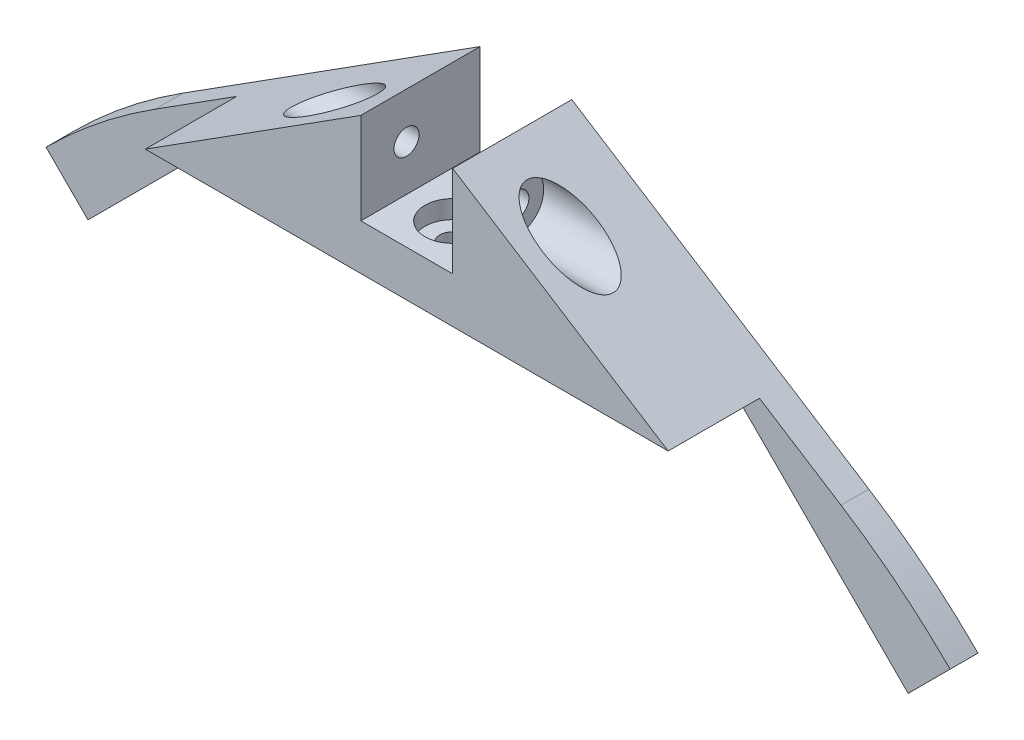
SolidWorks part; units mm, degrees
ref_plane "Front Plane" through (0, 0, 0) normal (0, 0, 1) x (1, 0, 0)
ref_plane "Top Plane" through (0, 0, 0) normal (0, 1, 0) x (1, 0, 0)
ref_plane "Right Plane" through (0, 0, 0) normal (1, 0, 0) x (0, 0, -1)
sketch "Sketch1" plane through (0, 0, 0) normal (0, 0, 1) x (1, 0, 0)
  line L0 (0, 284.5128) -> (0, -315.9314) construction
  line L1 (-464.297, 0) -> (544.589, 0) construction
  line L2 (-129.5, 50.1051) -> (-50.1051, 129.5)
  line L9 (-129.5, 50.1051) -> (-129.5, -50.1051)
  line L11 (-50.1051, -129.5) -> (50.1051, -129.5)
  line L13 (129.5, -50.1051) -> (129.5, 50.1051)
  line L15 (50.1051, 129.5) -> (-50.1051, 129.5)
  line L17 (50.1051, 129.5) -> (129.5, 50.1051)
  line L18 (129.5, -50.1051) -> (50.1051, -129.5)
  line L19 (-50.1051, -129.5) -> (-129.5, -50.1051)
  line L20 (-53.6407, 129.5) -> (-91.5703, 91.5703)
  line L21 (-91.5703, -91.5703) -> (-53.6407, -129.5)
  line L22 (53.6407, -129.5) -> (91.5703, -91.5703)
  line L23 (129.5, 53.6407) -> (91.5703, 91.5703)
  circle A0 centre (0, 0) radius 129.5 construction
  circle A2 centre (0, 0) radius 129.5
  circle A3 centre (0, 0) radius 109.75
  dimension "D2" = 259
  dimension "D3" = 219.5
  dimension "D1" = 0
  dimension "D4" = 259
  dimension "D5" = 254
  dimension "D6" = 4
sketch "Sketch2" plane through (0, 0, 0) normal (0, 0, 1) x (1, 0, 0)
  circle A2 centre (0, 0) radius 109.75
  circle A3 centre (0, 0) radius 129.5
  point P1 (114.75, 0)
  point P3 (0, 0)
  point P9 (104.9544, 32.0878)
  dimension "D1" = 219.5
  dimension "D2" = 259
sketch "Sketch3" plane through (0, 0, 0) normal (0, 0, 1) x (1, 0, 0)
  line L0 (0, 216.6703) -> (0, -179.3029) construction
  line L2 (0, 284.5128) -> (0, -315.9314) construction
  line L4 (-261.0178, 0) -> (186.7113, 0) construction
  line L5 (-464.297, 0) -> (544.589, 0) construction
  line L22 (-157.8941, 129.5) -> (159.8749, 129.5) construction
  line L23 (0, 0) -> (0, 188.0938) construction
  line L40 (-94.2678, 129.5) -> (106.7846, 129.5) construction
  line L41 (129.5, -10) -> (109.5, -10)
  line L42 (10, 129.5) -> (-10, 129.5)
  line L43 (10, 129.5) -> (10, 109.5)
  line L44 (10, 109.5) -> (-10, 109.5)
  line L45 (-10, 129.5) -> (-10, 109.5)
  line L46 (129.5, -10) -> (129.5, 10)
  line L47 (129.5, 10) -> (109.5, 10)
  line L48 (109.5, -10) -> (109.5, 10)
  line L49 (-10, -129.5) -> (-10, -109.5)
  line L50 (-10, -129.5) -> (10, -129.5)
  line L51 (10, -129.5) -> (10, -109.5)
  line L52 (-10, -109.5) -> (10, -109.5)
  line L53 (-129.5, 10) -> (-109.5, 10)
  line L54 (-129.5, 10) -> (-129.5, -10)
  line L55 (-129.5, -10) -> (-109.5, -10)
  line L56 (-109.5, 10) -> (-109.5, -10)
  line L57 (-22.9682, 119.5) -> (92.755, 119.5) construction
  circle A8 centre (-15, 119.5) radius 2.75
  circle A9 centre (15, 119.5) radius 2.75
  circle A10 centre (119.5, 15) radius 2.75
  circle A11 centre (119.5, -15) radius 2.75
  circle A12 centre (15, -119.5) radius 2.75
  circle A13 centre (-15, -119.5) radius 2.75
  circle A14 centre (-119.5, -15) radius 2.75
  circle A15 centre (-119.5, 15) radius 2.75
  dimension "D8" = 5.5
  dimension "D9" = 15
  dimension "D1" = 129.5
  dimension "D2" = 0
  dimension "D3" = 90
  dimension "D4" = 129.5
  dimension "D5" = 20
  dimension "D7" = 10
  dimension "D6" = 20
  dimension "D10" = 10
  dimension "D12" = 4
  dimension "D11" = 4
sketch "Sketch5" plane through (0, 0, 0) normal (0, 0, 1) x (1, 0, 0)
  line L0 (0, 161.9102) -> (0, -158.9824) construction
  line L1 (0, 284.5128) -> (0, -315.9314) construction
  line L11 (-129.5, 50.1051) -> (-50.1051, 129.5) construction
  line L12 (50.1051, 129.5) -> (-50.1051, 129.5) construction
  line L13 (50.1051, 129.5) -> (129.5, 50.1051) construction
  line L14 (-89.8026, 89.8026) -> (-50.1051, 129.5)
  line L15 (50.1051, 129.5) -> (-50.1051, 129.5)
  line L16 (50.1051, 129.5) -> (89.8026, 89.8026)
  line L17 (89.8026, 89.8026) -> (98.9949, 98.9949)
  line L18 (-89.8026, 89.8026) -> (-98.9949, 98.9949)
  arc A5 (98.9949, 98.9949) -> (-98.9949, 98.9949) centre (0, 0) ccw
  dimension "D2" = 280
extrude "Boss-Extrude4" add sketch "Sketch5" against normal blind 6.1
sketch "Sketch6" plane through (0, 0, 0) normal (0, 0, 1) x (1, 0, 0)
  line L0 (0, 251.9094) -> (0, -160.8611) construction
  line L1 (0, 284.5128) -> (0, -315.9314) construction
  line L2 (10.05, 139.5) -> (-10.05, 139.5)
  line L3 (-10.05, 139.5) -> (-10.05, 159.5)
  line L4 (-10.05, 159.5) -> (-50.1051, 130.7267)
  line L5 (-50.1051, 130.7267) -> (-50.1051, 129.5)
  line L6 (-50.1051, 129.5) -> (50.1051, 129.5)
  line L7 (50.1051, 129.5) -> (-50.1051, 129.5) construction
  line L8 (50.1051, 130.7267) -> (50.1051, 129.5)
  line L9 (10.05, 159.5) -> (50.1051, 130.7267)
  line L10 (10.05, 139.5) -> (10.05, 159.5)
  arc A0 (98.9949, 98.9949) -> (-98.9949, 98.9949) centre (0, 0) ccw construction
  point P18 (0, 129.5)
  point P21 (0, 139.5)
  dimension "D1" = 139.5
  dimension "D2" = 10.05
  dimension "D3" = 20
extrude "Boss-Extrude5" add sketch "Sketch6" along normal blind 20
sketch "Sketch7" plane through (0, 0, 0) normal (0, 0, 1) x (1, 0, 0)
  line L0 (-10.05, 159.5) -> (-75.1007, 118.152)
  line L1 (-129.5, 50.1051) -> (-50.1051, 129.5) construction
  line L2 (-98.9949, 98.9949) -> (-89.8026, 89.8026) construction
  line L3 (-89.8026, 89.8026) -> (-50.1051, 129.5)
  line L4 (-98.9949, 98.9949) -> (-89.8026, 89.8026)
  line L5 (0, 229.2061) -> (0, -18.2575) construction
  line L6 (0, 284.5128) -> (0, -315.9314) construction
  line L7 (89.8026, 89.8026) -> (50.1051, 129.5)
  line L8 (-10.05, 139.5) -> (-10.05, 159.5)
  line L9 (-10.05, 159.5) -> (-50.1051, 130.7267)
  line L10 (-50.1051, 130.7267) -> (-50.1051, 129.5)
  line L11 (-50.1051, 129.5) -> (50.1051, 129.5)
  line L12 (50.1051, 129.5) -> (50.1051, 130.7267)
  line L13 (50.1051, 130.7267) -> (10.05, 159.5)
  line L14 (10.05, 159.5) -> (10.05, 139.5)
  line L15 (10.05, 139.5) -> (-10.05, 139.5)
  line L16 (-10.05, 139.5) -> (-10.05, 159.5)
  line L19 (-50.1051, 129.5) -> (50.1051, 129.5)
  line L23 (10.05, 139.5) -> (-10.05, 139.5)
  line L24 (98.9949, 98.9949) -> (89.8026, 89.8026)
  line L25 (10.05, 139.5) -> (10.05, 159.5)
  line L26 (10.05, 159.5) -> (75.1007, 118.152)
  arc A0 (-50.1051, 130.7267) -> (-98.9949, 98.9949) centre (0, 0) ccw construction
  arc A1 (-75.1007, 118.152) -> (-98.9949, 98.9949) centre (0, 0) ccw
  arc A2 (75.1007, 118.152) -> (98.9949, 98.9949) centre (0, 0) cw
  point P18 (0, 129.5)
  point P24 (0, 139.5)
  dimension "D1" = 0
extrude "Boss-Extrude6" add sketch "Sketch7" against normal blind 6.1
sketch "Sketch8" plane through (0, 0, 0) normal (0, 0, 1) x (1, 0, 0)
  line L0 (-50.1051, 130.7267) -> (-50.1051, 129.5) construction
  line L1 (-10.05, 159.5) -> (-50.1051, 130.7267) construction
  line L2 (-10.05, 159.5) -> (-75.1007, 118.152) construction
  line L3 (-50.1051, 130.7267) -> (-50.1051, 129.5)
  line L4 (-10.05, 159.5) -> (-50.1051, 130.7267)
  line L5 (-10.05, 159.5) -> (-57.2474, 129.5)
  line L6 (-50.1051, 129.5) -> (-57.2474, 129.5)
  line L7 (-157.8941, 129.5) -> (159.8749, 129.5) construction
  line L8 (0, 197.1795) -> (0, 66.5763) construction
  line L9 (0, 284.5128) -> (0, -315.9314) construction
  line L10 (50.1051, 129.5) -> (57.2474, 129.5)
  line L11 (10.05, 159.5) -> (57.2474, 129.5)
  line L12 (10.05, 159.5) -> (50.1051, 130.7267)
  line L13 (50.1051, 130.7267) -> (50.1051, 129.5)
extrude "Boss-Extrude7" add sketch "Sketch8" along normal blind 20
sketch "Sketch9" plane through (0, 0, 0) normal (0, 0, 1) x (1, 0, 0)
  line L0 (10.05, 139.5) -> (-10.05, 139.5) construction
  line L1 (10.05, 139.5) -> (-10.05, 139.5)
  line L2 (-10.05, 139.5) -> (-10.05, 149.5)
  line L3 (-10.05, 139.5) -> (-10.05, 159.5) construction
  line L4 (-10.05, 149.5) -> (10.05, 149.5)
  line L5 (10.05, 159.5) -> (10.05, 139.5) construction
  line L6 (10.05, 149.5) -> (10.05, 139.5)
extrude "Cut-Extrude1" cut sketch "Sketch9" against normal through all both and the other way through all
sketch "Sketch10" plane through (0, 139.5, 0) normal (0, 1, 0) x (1, 0, 0)
  line L0 (0, 27.3303) -> (0, -27.1161) construction
  line L1 (10.05, -20) -> (-10.05, -20) construction
  circle A0 centre (0, -10) radius 2.75
  dimension "D1" = 5.5
  dimension "D2" = 10
extrude "Cut-Extrude2" cut sketch "Sketch10" against normal blind 20
sketch "Sketch11" plane through (0, 139.5, 0) normal (0, 1, 0) x (1, 0, 0)
  circle A0 centre (0, -10) radius 6
  dimension "D1" = 12
extrude "Cut-Extrude3" cut sketch "Sketch11" against normal blind 4
sketch "Sketch12" plane through (0, 0, 0) normal (1, 0, 0) x (0, 0, -1)
  line L0 (-41.9419, 149.5) -> (44.6817, 149.5) construction
  line L1 (-20, 129.5) -> (-20, 159.5) construction
  circle A0 centre (-10, 149.5) radius 2.75
  dimension "D2" = 5.5
  dimension "D3" = 10
  dimension "D1" = 149.5
extrude "Cut-Extrude4" cut sketch "Sketch12" against normal through all both and the other way through all
ref_plane "Plane1" through (14, 0, 0) normal (1, 0, 0) x (0, 0, -1)
sketch "Sketch13" plane through (14, 0, 0) normal (1, 0, 0) x (0, 0, -1)
  circle A0 centre (-10, 149.5) radius 6
  dimension "D1" = 12
extrude "Cut-Extrude5" cut sketch "Sketch13" along normal through all
ref_plane "Plane2" through (-14, 0, 0) normal (1, 0, 0) x (0, 0, -1)
sketch "Sketch14" plane through (-14, 0, 0) normal (1, 0, 0) x (0, 0, -1)
  circle A0 centre (-10, 149.5) radius 6
  dimension "D1" = 12
extrude "Cut-Extrude6" cut sketch "Sketch14" against normal through all
